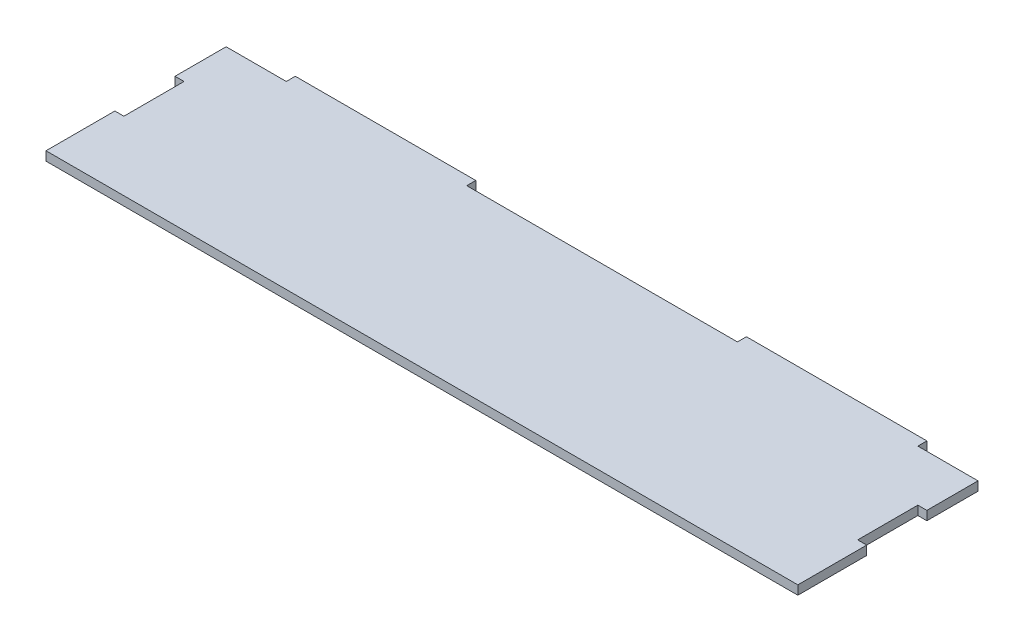
SolidWorks part; units mm, degrees
ref_plane "Front Plane" through (0, 0, 0) normal (0, 0, 1) x (1, 0, 0)
ref_plane "Top Plane" through (0, 0, 0) normal (0, 1, 0) x (1, 0, 0)
ref_plane "Right Plane" through (0, 0, 0) normal (1, 0, 0) x (0, 0, -1)
sketch "Sketch1" plane through (0, 0, 0) normal (0, 1, 0) x (1, 0, 0)
  line L1 (0, 0) -> (250, 0)
  line L2 (0, 0) -> (0, 62.9)
  line L3 (0, 62.9) -> (250, 62.9)
  line L4 (250, 0) -> (250, 62.9)
  dimension "D1" = 250
  dimension "D2" = 62.9
extrude "Boss-Extrude1" add sketch "Sketch1" along normal blind 3
sketch "Sketch3" plane through (0, 3, 0) normal (0, 1, 0) x (1, 0, 0)
  line L0 (0, 62.9) -> (0, 0) construction
  line L1 (0, 42.9) -> (3, 42.9)
  line L2 (0, 42.9) -> (0, 22.9)
  line L3 (0, 22.9) -> (3, 22.9)
  line L4 (3, 42.9) -> (3, 22.9)
  line L5 (250, 0) -> (250, 62.9) construction
  line L6 (250, 42.9) -> (247, 42.9)
  line L7 (250, 42.9) -> (250, 22.9)
  line L8 (250, 22.9) -> (247, 22.9)
  line L9 (247, 42.9) -> (247, 22.9)
  line L10 (250, 62.9) -> (0, 62.9) construction
  dimension "D1" = 3
  dimension "D2" = 3
  dimension "D3" = 20
  dimension "D4" = 20
  dimension "D5" = 20
  dimension "D6" = 20
extrude "Cut-Extrude1" cut sketch "Sketch3" against normal through all
sketch "Sketch4" plane through (0, 3, 0) normal (0, 1, 0) x (1, 0, 0)
  line L1 (0, 62.9) -> (20, 62.9)
  line L2 (0, 62.9) -> (0, 59.9)
  line L3 (0, 59.9) -> (20, 59.9)
  line L4 (20, 62.9) -> (20, 59.9)
  dimension "D1" = 3
  dimension "D2" = 20
extrude "Cut-Extrude2" cut sketch "Sketch4" against normal up to next
sketch "Sketch5" plane through (0, 3, 0) normal (0, 1, 0) x (1, 0, 0)
  line L1 (250, 62.9) -> (230, 62.9)
  line L2 (250, 62.9) -> (250, 59.9)
  line L3 (250, 59.9) -> (230, 59.9)
  line L4 (230, 62.9) -> (230, 59.9)
  dimension "D1" = 3
  dimension "D2" = 20
extrude "Cut-Extrude3" cut sketch "Sketch5" against normal up to next
sketch "Sketch6" plane through (0, 3, 0) normal (0, 1, 0) x (1, 0, 0)
  line L0 (230, 62.9) -> (20, 62.9) construction
  line L1 (80, 62.9) -> (170, 62.9)
  line L2 (80, 62.9) -> (80, 59.9)
  line L3 (80, 59.9) -> (170, 59.9)
  line L4 (170, 62.9) -> (170, 59.9)
  line L5 (0, 59.9) -> (0, 42.9) construction
  dimension "D1" = 3
  dimension "D2" = 80
  dimension "D3" = 80
extrude "Cut-Extrude4" cut sketch "Sketch6" against normal up to next
